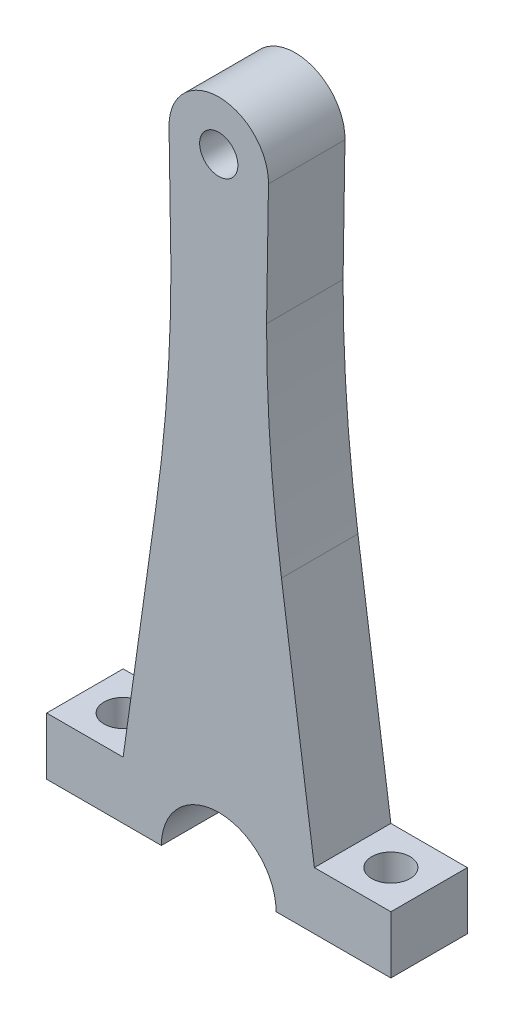
SolidWorks part; units mm, degrees
ref_plane "Front Plane" through (0, 0, 0) normal (0, 0, 1) x (1, 0, 0)
ref_plane "Top Plane" through (0, 0, 0) normal (0, 1, 0) x (1, 0, 0)
ref_plane "Right Plane" through (0, 0, 0) normal (1, 0, 0) x (0, 0, -1)
sketch "Sketch2" plane through (0, 0, 0) normal (0, 0, 1) x (1, 0, 0)
  line L0 (-15, 0) -> (-45, 0)
  line L1 (-45, 0) -> (-45, 15)
  line L2 (-45, 15) -> (-25, 15)
  line L3 (0, 15) -> (0, 134.4625) construction
  line L4 (-25, 15) -> (-16.3928, 76.2436)
  line L5 (-12.5, 131.9128) -> (-12.9984, 163.7968)
  line L6 (12.5, 131.9128) -> (12.9984, 163.7968)
  line L7 (0, 134.4625) -> (0, 164) construction
  line L8 (25, 15) -> (45, 15)
  line L9 (45, 15) -> (45, 0)
  line L10 (45, 0) -> (15, 0)
  line L11 (0, 0) -> (0, 15)
  line L12 (-12.9984, 163.7968) -> (12.9984, 163.7968) construction
  line L13 (16.3928, 76.2436) -> (25, 15)
  arc A0 (15, 0) -> (-15, 0) centre (0, 0) ccw
  arc A1 (16.3928, 76.2436) -> (12.5, 131.9128) centre (412.5, 131.9128) cw
  arc A2 (-16.3928, 76.2436) -> (-12.5, 131.9128) centre (-412.5, 131.9128) ccw
  arc A3 (12.9984, 163.7968) -> (-12.9984, 163.7968) centre (0, 164) ccw
  circle A4 centre (0, 164) radius 5
  dimension "D1" = 30
  dimension "D8" = 8
  dimension "D10" = 400
  dimension "D11" = 26
  dimension "D6" = 10
  dimension "D2" = 45
  dimension "D3" = 45
  dimension "D4" = 20
  dimension "D5" = 15
  dimension "D12" = 149
extrude "Boss-Extrude2" add sketch "Sketch2" along normal blind 20 contours L6 A3 L5 A2 L4 L2 L1 L0 A0 L10 L9 L8 L13 A1 A4
hole_wizard "Ø1.0mm Dowel Hole1" positions "Sketch5" profile "Sketch6" hole size "Ø1.0" standard "ISO" end condition through all
sketch "Sketch5" plane through (0, 15, 0) normal (0, 1, 0) x (1, 0, 0)
  line L1 (-35, -10) -> (35, -10) construction
  line L3 (-45, 0) -> (-25, 0) construction
  line L4 (0, 0) -> (0, -38.4999) construction
  point P0 (-35, -10)
  point P2 (35, -10)
  dimension "D1" = 10
  dimension "D2" = 70
  dimension "D3" = 35
sketch "Sketch6" plane through (-35, 15, 10) normal (1, 0, 0) x (0, 0, 1)
  line L0 (0, 0) -> (0, 15)
  line L1 (0, 15) -> (5, 15)
  line L2 (5, 15) -> (5, 0)
  line L5 (5, 0) -> (0, 0)
  line L11 (0, -6.35) -> (0, 107.95) construction
  dimension "Thru Hole Dia." = 10
  dimension "Thru Hole Depth" = 15
